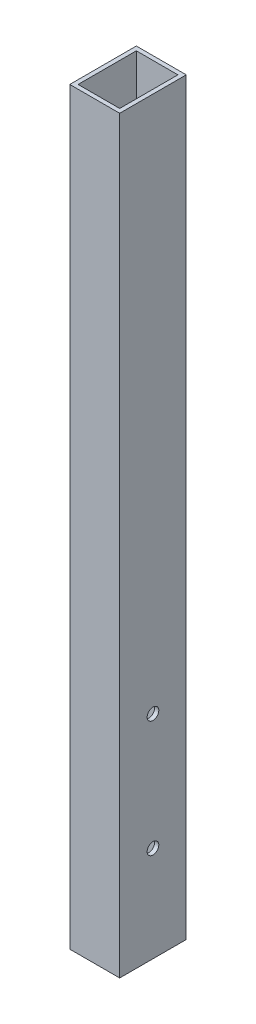
SolidWorks part; units mm, degrees
material "AISI 304"
ref_plane "Front Plane" through (0, 0, 0) normal (0, 0, 1) x (1, 0, 0)
ref_plane "Top Plane" through (0, 0, 0) normal (0, 1, 0) x (1, 0, 0)
ref_plane "Right Plane" through (0, 0, 0) normal (1, 0, 0) x (0, 0, -1)
sketch "Sketch1" plane through (0, 0, 0) normal (0, 1, 0) x (1, 0, 0)
  line L1 (38.1, -50.8) -> (-38.1, -50.8)
  line L2 (38.1, -50.8) -> (38.1, 50.8)
  line L3 (38.1, 50.8) -> (-38.1, 50.8)
  line L4 (-38.1, -50.8) -> (-38.1, 50.8)
  line L5 (38.1, -50.8) -> (-38.1, 50.8) construction
  line L6 (38.1, 50.8) -> (-38.1, -50.8) construction
  point P0 (0, 0)
  dimension "D1" = 76.2
  dimension "D2" = 101.6
extrude "Boss-Extrude1" add sketch "Sketch1" against normal blind 1143
sketch "Sketch2" plane through (0, -1143, 0) normal (0, -1, 0) x (1, 0, 0)
  line L0 (-38.1, 50.8) -> (38.1, 50.8) construction
  line L1 (-31.75, 44.45) -> (31.75, 44.45)
  line L2 (-31.75, 44.45) -> (-31.75, -44.45)
  line L3 (-31.75, -44.45) -> (31.75, -44.45)
  line L4 (31.75, 44.45) -> (31.75, -44.45)
  line L5 (-31.75, 44.45) -> (31.75, -44.45) construction
  line L6 (-31.75, -44.45) -> (31.75, 44.45) construction
  line L7 (38.1, 50.8) -> (38.1, -50.8) construction
  point P0 (0, 0)
  dimension "D1" = 6.35
  dimension "D2" = 6.35
extrude "Cut-Extrude1" cut sketch "Sketch2" against normal through all
sketch "Sketch3" plane through (38.1, 0, 0) normal (1, 0, 0) x (0, 0, -1)
  line L0 (-50.8, -1143) -> (50.8, -1143) construction
  circle A0 centre (0, -996.95) radius 8.89
  circle A1 centre (0, -819.15) radius 8.89
  dimension "D1" = 17.78
  dimension "D2" = 17.78
  dimension "D3" = 177.8
  dimension "D4" = 146.05
extrude "Cut-Extrude2" cut sketch "Sketch3" against normal through all
